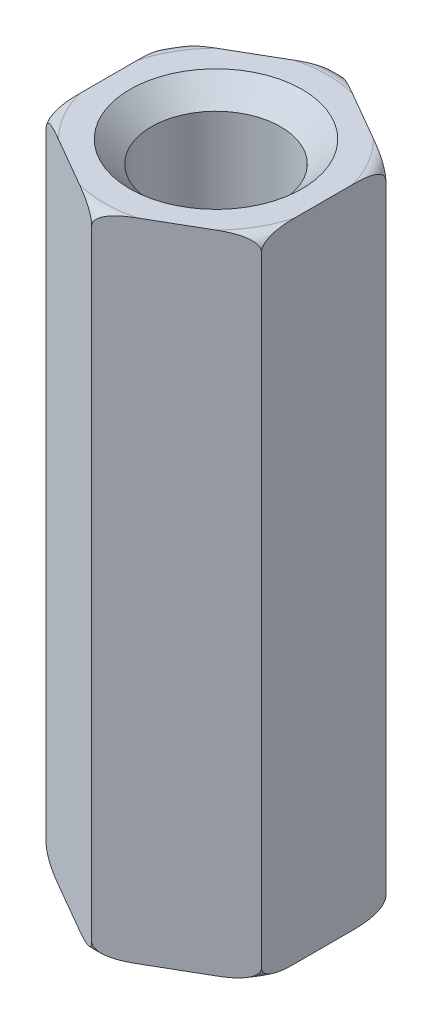
SolidWorks part; units mm, degrees
ref_plane "Front Plane" through (0, 0, 0) normal (0, 0, 1) x (1, 0, 0)
ref_plane "Top Plane" through (0, 0, 0) normal (0, 1, 0) x (1, 0, 0)
ref_plane "Right Plane" through (0, 0, 0) normal (1, 0, 0) x (0, 0, -1)
sketch "Sketch2" plane through (0, 0, 0) normal (0, 1, 0) x (1, 0, 0)
  line L1 (0, -2.8868) -> (2.5, -1.4434)
  line L2 (2.5, -1.4434) -> (2.5, 1.4434)
  line L3 (2.5, 1.4434) -> (0, 2.8868)
  line L4 (0, 2.8868) -> (-2.5, 1.4434)
  line L5 (-2.5, 1.4434) -> (-2.5, -1.4434)
  line L6 (-2.5, -1.4434) -> (0, -2.8868)
  circle A0 centre (0, 0) radius 2.5 construction
  circle A1 centre (0, 0) radius 1.5
  dimension "D1" = 3
  dimension "D2" = 5
extrude "Boss-Extrude2" add sketch "Sketch2" along normal mid plane 15 contours A1
chamfer "Chamfer1" distance 0.5 angle 45 2 edges at (0, -7.5, 1.5) (0, 7.5, 1.5)
sketch "Sketch4" plane through (0, 0, 0) normal (1, 0, 0) x (0, 0, -1)
  line L1 (-2.8868, 7.5) -> (-2.8868, -7.5) construction
  line L3 (-2.8868, 7.5) -> (-1.4434, 7.5) construction
  line L4 (-2.8868, 7.2) -> (-2.8868, 7.5)
  line L5 (-2.8868, 7.5) -> (-2.5868, 7.5)
  arc A0 (-2.8868, 7.2) -> (-2.5868, 7.5) centre (-2.5868, 7.2) cw
  dimension "D1" = 0.3
ref_axis "Axis1" through (0, 57.75, 0) along (0, -1, 0)
revolve "Cut-Revolve1" cut sketch "Sketch4" angle 360 about axis through (0, 57.75, 0) along (0, -1, 0)
mirror "Mirror1" about plane through (0, 0, 0) normal (0, 1, 0) of "Cut-Revolve1"
